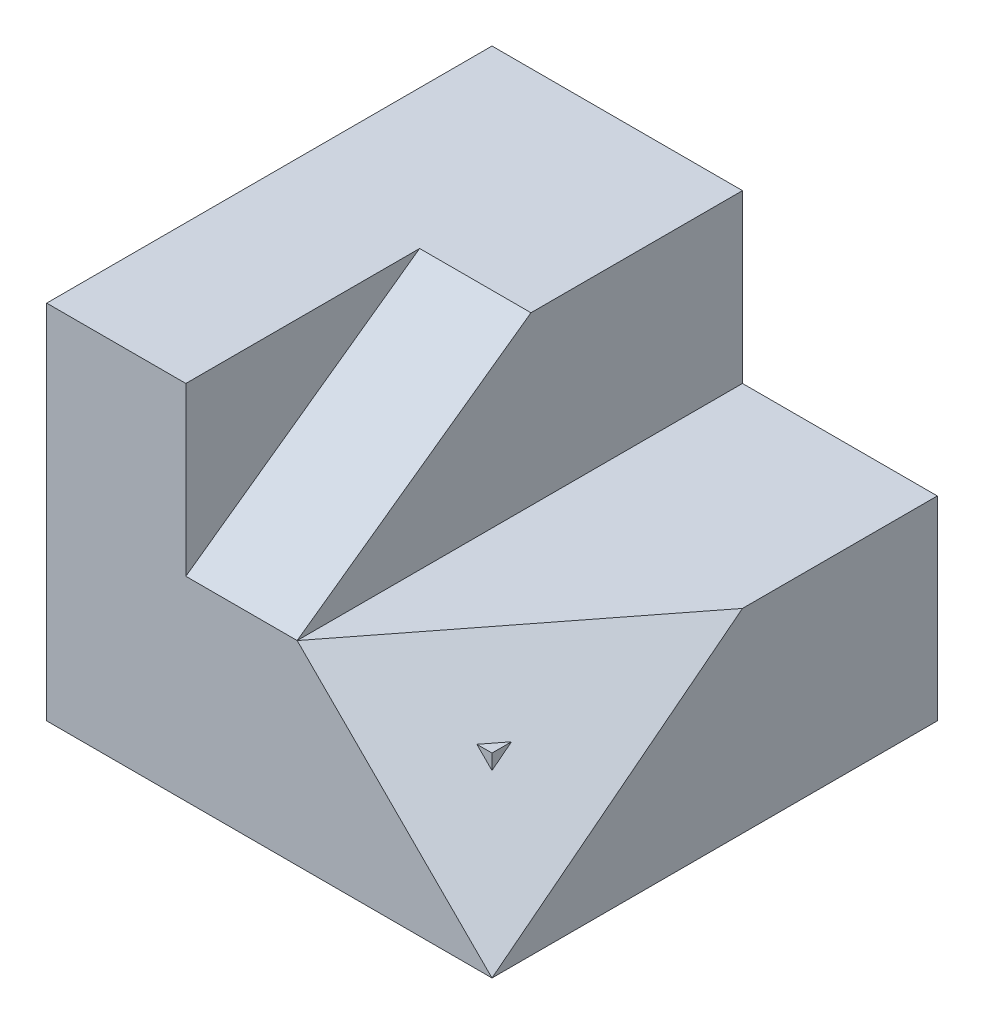
SolidWorks part; units mm, degrees
ref_plane "Front Plane" through (0, 0, 0) normal (0, 0, 1) x (1, 0, 0)
ref_plane "Top Plane" through (0, 0, 0) normal (0, 1, 0) x (1, 0, 0)
ref_plane "Right Plane" through (0, 0, 0) normal (1, 0, 0) x (0, 0, -1)
sketch "Sketch1" plane through (0, 0, 0) normal (0, 0, 1) x (1, 0, 0)
  line L1 (-40, 32.5) -> (40, 32.5)
  line L2 (-40, 32.5) -> (-40, -32.5)
  line L3 (-40, -32.5) -> (40, -32.5)
  line L4 (40, 32.5) -> (40, -32.5)
  line L5 (-40, 32.5) -> (40, -32.5) construction
  line L6 (-40, -32.5) -> (40, 32.5) construction
  point P0 (0, 0)
  dimension "D1" = 65
  dimension "D2" = 80
extrude "Boss-Extrude1" add sketch "Sketch1" against normal blind 80
sketch "Sketch2" plane through (40, 0, 0) normal (1, 0, 0) x (0, 0, -1)
  line L0 (80, -32.5) -> (80, 32.5) construction
  line L1 (0, 32.5) -> (80, 32.5)
  line L2 (0, 32.5) -> (0, 2.5)
  line L3 (0, 2.5) -> (80, 2.5)
  line L4 (80, 32.5) -> (80, 2.5)
  dimension "D1" = 30
extrude "Cut-Extrude1" cut sketch "Sketch2" against normal blind 35
sketch "Sketch3" plane through (5, 0, 0) normal (1, 0, 0) x (0, 0, -1)
  line L0 (0, 32.5) -> (42, 32.5)
  line L1 (80, 32.5) -> (0, 32.5) construction
  line L2 (42, 32.5) -> (0, 2.5)
  line L3 (0, 32.5) -> (0, 2.5) construction
  line L4 (0, 32.5) -> (0, 2.5)
  line L5 (80, 32.5) -> (0, 32.5)
  line L6 (0, 2.5) -> (80, 2.5) construction
  point P4 (0, 2.5)
  line M2 (0, 32.5) -> (0, 2.5)
  line M5 (80, 32.5) -> (0, 32.5)
  dimension "D1" = 38
extrude "Cut-Extrude2" cut sketch "Sketch3" against normal blind 20 contours L2 M5 M2
sketch3d "3DSketch2"
  line L0 (5, 2.5, 0) -> (40, 2.5, -45) construction
  line L2 (40, 2.5, 0) -> (40, 2.5, -80) construction
  line L3 (40, 2.5, -45) -> (40, -32.5, 0) construction
  line L4 (40, -32.5, 0) -> (40, 2.5, 0) construction
  line L5 (40, -32.5, -80) -> (40, -32.5, 0) construction
  line L6 (40, -32.5, 0) -> (5, 2.5, 0) construction
  dimension "D1" = 35
ref_plane "Plane1" through (2.8791, 2.8791, 2.2393) normal (0.6196, 0.6196, 0.4819) x (0.7849, -0.4891, -0.3804)
sketch "Sketch6" plane through (2.8791, 2.8791, 2.2393) normal (0.6196, 0.6196, 0.4819) x (0.7849, -0.4891, -0.3804)
  line L0 (47.292, 37.0557) -> (47.292, -19.9531) construction
  line L1 (47.292, 37.0557) -> (47.292, -19.9531)
  line L2 (47.292, -19.9531) -> (2.702, 1.5349) construction
  line L3 (47.292, -19.9531) -> (2.702, 1.5349)
  line L4 (2.702, 1.5349) -> (47.292, 37.0557) construction
  line L5 (2.702, 1.5349) -> (47.292, 37.0557)
extrude "Cut-Extrude8" cut sketch "Sketch6" along normal blind 20
